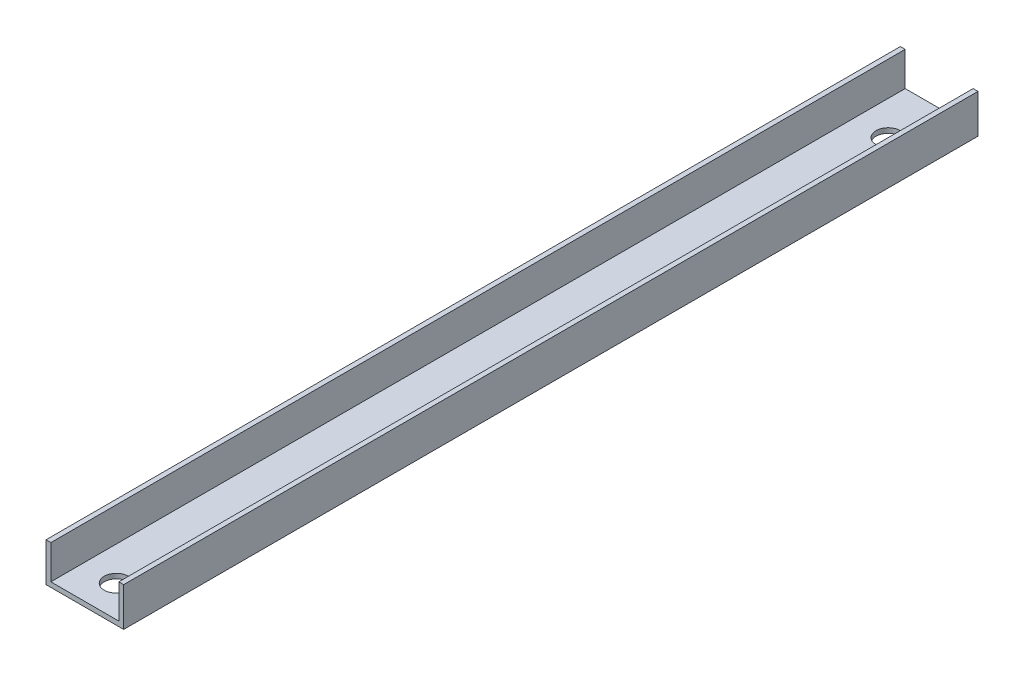
SolidWorks part; units mm, degrees
ref_plane "Front Plane" through (0, 0, 0) normal (0, 0, 1) x (1, 0, 0)
ref_plane "Top Plane" through (0, 0, 0) normal (0, 1, 0) x (1, 0, 0)
ref_plane "Right Plane" through (0, 0, 0) normal (1, 0, 0) x (0, 0, -1)
sketch "Sketch1" plane through (0, 0, 0) normal (0, 0, 1) x (1, 0, 0)
  line L0 (-22.225, -9.525) -> (-22.225, 12.7)
  line L1 (-25.4, -12.7) -> (25.4, -12.7)
  line L2 (-25.4, -12.7) -> (-25.4, 12.7)
  line L3 (-22.225, -9.525) -> (22.225, -9.525)
  line L4 (25.4, -12.7) -> (25.4, 12.7)
  line L5 (22.225, -9.525) -> (22.225, 12.7)
  line L6 (-25.4, 12.7) -> (-22.225, 12.7)
  line L7 (22.225, 12.7) -> (25.4, 12.7)
  dimension "D1" = 25.4
  dimension "D2" = 50.8
  dimension "D3" = 3.175
extrude "Boss-Extrude1" add sketch "Sketch1" along normal blind 558.8
sketch "Sketch2" plane through (0, -12.7, 0) normal (0, -1, 0) x (1, 0, 0)
  line L0 (0, 0) -> (0, 25.4) construction
  line L1 (-25.4, 0) -> (25.4, 0) construction
  circle A0 centre (0, 33.3375) radius 7.9375
  dimension "D2" = 15.875
  dimension "D1" = 25.4
extrude "Cut-Extrude1" cut sketch "Sketch2" against normal up to next
sketch "Sketch3" plane through (0, -12.7, 0) normal (0, -1, 0) x (1, 0, 0)
  line L0 (0, 558.8) -> (0, 546.1) construction
  line L1 (-25.4, 558.8) -> (25.4, 558.8) construction
  circle A0 centre (0, 538.1625) radius 7.9375
  dimension "D1" = 12.7
extrude "Cut-Extrude2" cut sketch "Sketch3" against normal up to next
